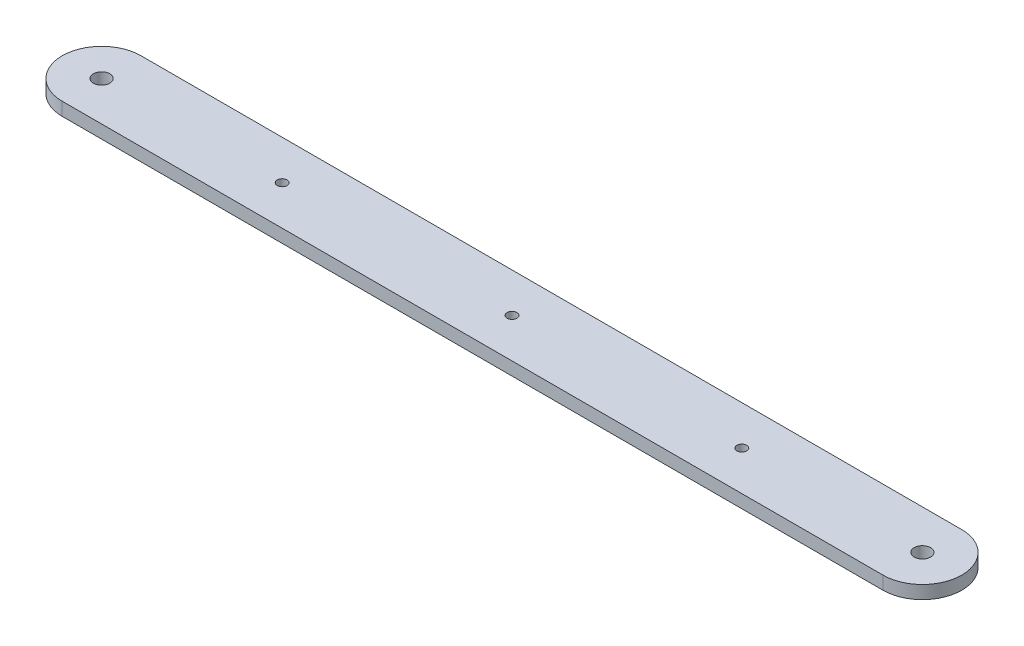
SolidWorks part; units mm, degrees
ref_plane "前视基准面" through (0, 0, 0) normal (0, 0, 1) x (1, 0, 0)
ref_plane "上视基准面" through (0, 0, 0) normal (0, 1, 0) x (1, 0, 0)
ref_plane "右视基准面" through (0, 0, 0) normal (1, 0, 0) x (0, 0, -1)
other "Configuration Table"
sketch "草图1" plane through (0, 0, 0) normal (0, 1, 0) x (1, 0, 0)
  line L0 (-125, 0) -> (125, 0) construction
  line L1 (-125, 12) -> (125, 12)
  line L2 (-125, -12) -> (125, -12)
  arc A0 (-125, 12) -> (-125, -12) centre (-125, 0) ccw
  arc A1 (125, -12) -> (125, 12) centre (125, 0) ccw
  circle A2 centre (125, 0) radius 2.5
  circle A3 centre (-125, 0) radius 2.5
  point P2 (0, 0)
  dimension "D2" = 12
  dimension "D3" = 5
  dimension "D1" = 250
extrude "凸台-拉伸1" add sketch "草图1" along normal blind 4
sketch "草图2" plane through (0, 0, 0) normal (0, -1, 0) x (1, 0, 0)
  line L0 (-70, 0) -> (70, 0) construction
  circle A0 centre (-70, 0) radius 1.5
  circle A1 centre (0, 0) radius 1.5
  circle A2 centre (70, 0) radius 1.5
  point P4 (0, 0)
  dimension "D2" = 3
  dimension "D1" = 140
extrude "切除-拉伸1" cut sketch "草图2" against normal blind 4
